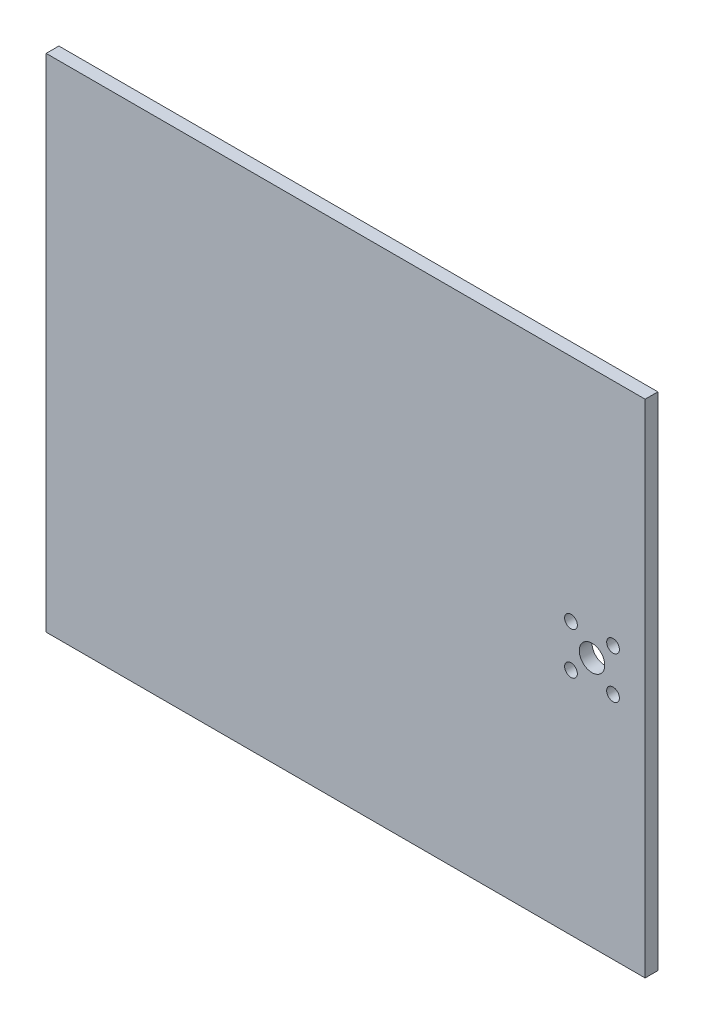
SolidWorks part; units mm, degrees
ref_plane "前视基准面" through (0, 0, 0) normal (0, 0, 1) x (1, 0, 0)
ref_plane "上视基准面" through (0, 0, 0) normal (0, 1, 0) x (1, 0, 0)
ref_plane "右视基准面" through (0, 0, 0) normal (1, 0, 0) x (0, 0, -1)
other "Configuration Table"
sketch "草图1" plane through (0, 0, 0) normal (0, 0, 1) x (1, 0, 0)
  line L1 (150, -59) -> (-150, -59)
  line L2 (150, -59) -> (150, 59)
  line L3 (150, 59) -> (-150, 59)
  line L4 (-150, -59) -> (-150, 59)
  line L5 (150, -59) -> (-150, 59) construction
  line L6 (150, 59) -> (-150, -59) construction
  point P0 (0, 0)
  dimension "D1" = 118
  dimension "D2" = 300
extrude "凸台-拉伸1" add sketch "草图1" along normal blind 3
sketch "草图2" plane through (0, 0, 0) normal (0, 0, -1) x (-1, 0, 0)
  circle A0 centre (-142.4497, 4.9497) radius 1.5
  circle A1 centre (-132.5503, 4.9497) radius 1.5
  circle A2 centre (-137.5, 0) radius 3
  circle A3 centre (-142.4497, -4.9497) radius 1.5
  circle A4 centre (-132.5503, -4.9497) radius 1.5
extrude "切除-拉伸1" cut sketch "草图2" against normal blind 3
sketch "草图6" plane through (0, 0, 3) normal (0, 0, 1) x (1, 0, 0)
  line L0 (-150, -59) -> (150, -59) construction
  line L1 (-150, 59) -> (9, 59)
  line L2 (-150, 59) -> (-150, -59)
  line L3 (-150, -59) -> (9, -59)
  line L4 (9, 59) -> (9, -59)
  dimension "D1" = 159
extrude "切除-拉伸2" cut sketch "草图6" against normal blind 10
